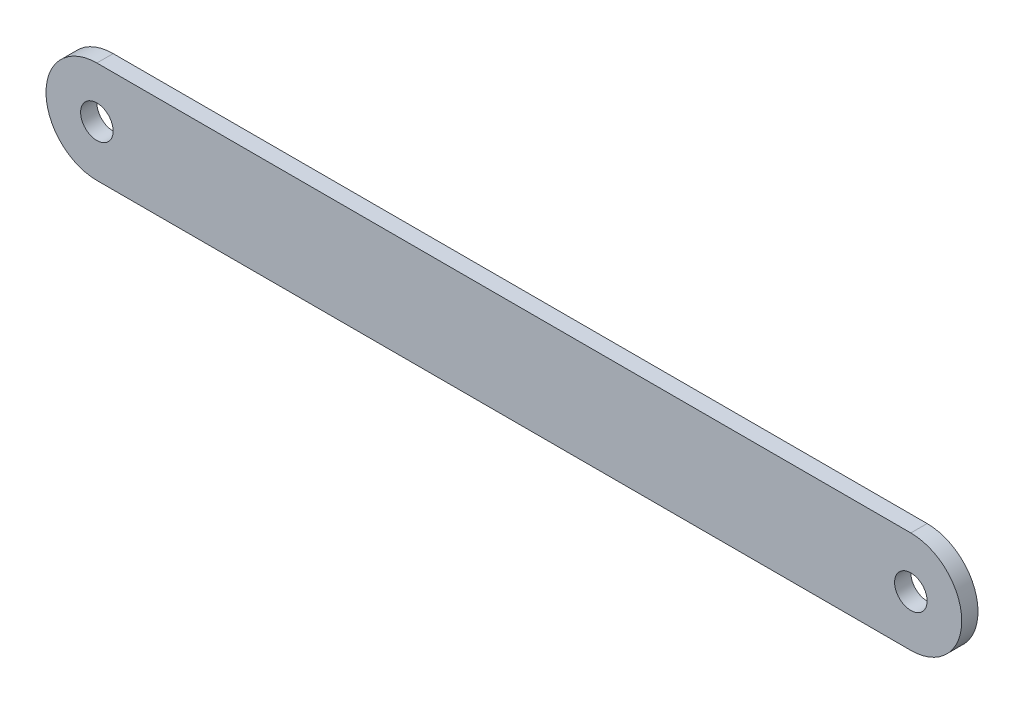
SolidWorks part; units mm, degrees
material "Oak"
ref_plane "Front Plane" through (0, 0, 0) normal (0, 0, 1) x (1, 0, 0)
ref_plane "Top Plane" through (0, 0, 0) normal (0, 1, 0) x (1, 0, 0)
ref_plane "Right Plane" through (0, 0, 0) normal (1, 0, 0) x (0, 0, -1)
sketch "Sketch1" plane through (0, 0, 0) normal (0, 0, 1) x (1, 0, 0)
  line L0 (-41.0042, 0) -> (158.9958, 0) construction
  line L1 (-41.0042, 12.5) -> (158.9958, 12.5)
  line L2 (-41.0042, -12.5) -> (158.9958, -12.5)
  arc A0 (-41.0042, 12.5) -> (-41.0042, -12.5) centre (-41.0042, 0) ccw
  arc A1 (158.9958, -12.5) -> (158.9958, 12.5) centre (158.9958, 0) ccw
  circle A2 centre (-41.0042, 0) radius 4
  circle A3 centre (158.9958, 0) radius 4
  point P3 (58.9958, 0)
  point P12 (0, 0)
  dimension "D1" = 25
  dimension "D2" = 200
extrude "Boss-Extrude1" add sketch "Sketch1" along normal blind 4
